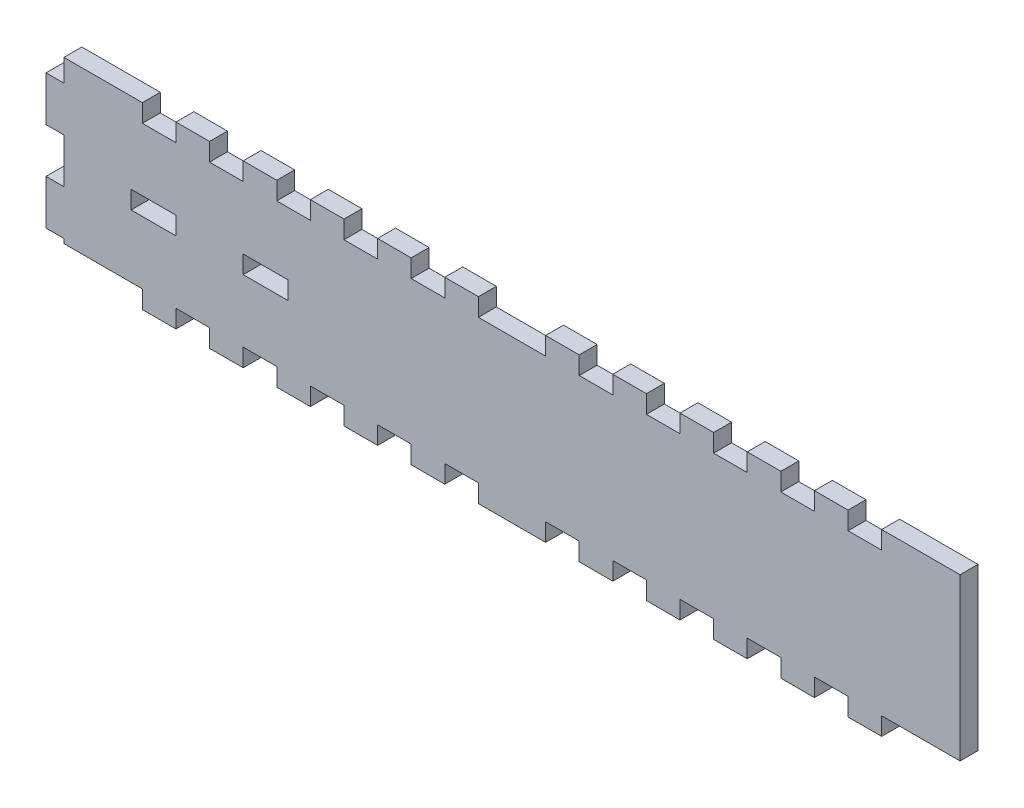
SolidWorks part; units mm, degrees
ref_plane "Plan de face" through (0, 0, 0) normal (0, 0, 1) x (1, 0, 0)
ref_plane "Plan de dessus" through (0, 0, 0) normal (0, 1, 0) x (1, 0, 0)
ref_plane "Plan de droite" through (0, 0, 0) normal (1, 0, 0) x (0, 0, -1)
sketch "Esquisse1" plane through (0, 0, 0) normal (0, 0, 1) x (1, 0, 0)
  line L1 (-200, -40) -> (200, -40)
  line L2 (-200, -40) -> (-200, 40)
  line L3 (-200, 40) -> (200, 40)
  line L4 (200, -40) -> (200, 40)
  line L5 (-200, -40) -> (200, 40) construction
  line L6 (-200, 40) -> (200, -40) construction
  point P0 (0, 0)
  dimension "D1" = 400
  dimension "D2" = 80
extrude "Boss.-Extru.1" add sketch "Esquisse1" along normal blind 8
sketch "Esquisse2" plane through (0, 0, 0) normal (0, 0, 1) x (1, 0, 0)
  line L0 (-200, 40) -> (-200, -40) construction
  line L1 (-200, 10) -> (-208, 10)
  line L2 (-200, 10) -> (-200, 30)
  line L3 (-200, 30) -> (-208, 30)
  line L4 (-208, 10) -> (-208, 30)
  line L5 (-200, 0) -> (-152.7974, 0) construction
  line L6 (-200, -30) -> (-208, -30)
  line L7 (-208, -10) -> (-208, -30)
  line L8 (-200, -10) -> (-208, -10)
  line L9 (-200, -10) -> (-200, -30)
  point P6 (-200, 0)
  dimension "D1" = 10
  dimension "D2" = 20
  dimension "D3" = 8
extrude "Boss.-Extru.2" add sketch "Esquisse2" along normal blind 8
sketch "Esquisse4" plane through (0, 0, 0) normal (0, 0, 1) x (1, 0, 0)
  line L0 (200, 40) -> (-200, 40) construction
  line L1 (0, 40) -> (-15, 40)
  line L3 (0, 32) -> (-15, 32)
  line L4 (-15, 40) -> (-15, 32)
  line L5 (-30, 40) -> (-30, 32)
  line L6 (-30, 40) -> (-45, 40)
  line L7 (-45, 40) -> (-45, 32)
  line L8 (-30, 32) -> (-45, 32)
  line L9 (-60, 40) -> (-60, 32)
  line L10 (-60, 40) -> (-75, 40)
  line L11 (-75, 40) -> (-75, 32)
  line L12 (-60, 32) -> (-75, 32)
  line L13 (-90, 40) -> (-90, 32)
  line L14 (-90, 40) -> (-105, 40)
  line L15 (-105, 40) -> (-105, 32)
  line L16 (-90, 32) -> (-105, 32)
  line L17 (-120, 40) -> (-120, 32)
  line L18 (-120, 40) -> (-135, 40)
  line L19 (-135, 40) -> (-135, 32)
  line L20 (-120, 32) -> (-135, 32)
  line L21 (-150, 40) -> (-150, 32)
  line L22 (-150, 40) -> (-165, 40)
  line L23 (-165, 40) -> (-165, 32)
  line L24 (-150, 32) -> (-165, 32)
  line L25 (0, 0) -> (0, 21.1046) construction
  line L26 (30, 40) -> (45, 40)
  line L27 (45, 40) -> (45, 32)
  line L28 (30, 32) -> (45, 32)
  line L29 (30, 40) -> (30, 32)
  line L30 (60, 40) -> (75, 40)
  line L31 (75, 40) -> (75, 32)
  line L32 (60, 32) -> (75, 32)
  line L33 (60, 40) -> (60, 32)
  line L34 (90, 40) -> (105, 40)
  line L35 (105, 40) -> (105, 32)
  line L36 (90, 32) -> (105, 32)
  line L37 (90, 40) -> (90, 32)
  line L38 (120, 40) -> (135, 40)
  line L39 (135, 40) -> (135, 32)
  line L40 (120, 32) -> (135, 32)
  line L41 (120, 40) -> (120, 32)
  line L42 (150, 40) -> (165, 40)
  line L43 (165, 40) -> (165, 32)
  line L44 (150, 32) -> (165, 32)
  line L45 (150, 40) -> (150, 32)
  line L47 (0, 40) -> (15, 40)
  line L49 (0, 32) -> (15, 32)
  line L50 (15, 40) -> (15, 32)
  dimension "D1" = 15
  dimension "D2" = 8
  dimension "D4" = 15
  dimension "D3" = 6
extrude "Enlèv. mat.-Extru.1" cut sketch "Esquisse4" along normal through all
sketch "Esquisse5" plane through (0, 0, 0) normal (0, 0, 1) x (1, 0, 0)
  line L0 (-200, -40) -> (200, -40) construction
  line L1 (-15, -40) -> (-30, -40)
  line L2 (-15, -40) -> (-15, -32)
  line L3 (-15, -32) -> (-30, -32)
  line L4 (-30, -40) -> (-30, -32)
  line L5 (-45, -40) -> (-45, -32)
  line L6 (-45, -40) -> (-60, -40)
  line L7 (-60, -40) -> (-60, -32)
  line L8 (-45, -32) -> (-60, -32)
  line L9 (-75, -40) -> (-75, -32)
  line L10 (-75, -40) -> (-90, -40)
  line L11 (-90, -40) -> (-90, -32)
  line L12 (-75, -32) -> (-90, -32)
  line L13 (-105, -40) -> (-105, -32)
  line L14 (-105, -40) -> (-120, -40)
  line L15 (-120, -40) -> (-120, -32)
  line L16 (-105, -32) -> (-120, -32)
  line L17 (-135, -40) -> (-135, -32)
  line L18 (-135, -40) -> (-150, -40)
  line L19 (-150, -40) -> (-150, -32)
  line L20 (-135, -32) -> (-150, -32)
  line L22 (0, 0) -> (0, -22.7254) construction
  line L23 (-200, -40) -> (-165, -40)
  line L24 (-200, -40) -> (-200, -32)
  line L25 (-200, -32) -> (-165, -32)
  line L26 (-165, -40) -> (-165, -32)
  line L27 (15, -32) -> (30, -32)
  line L28 (30, -40) -> (30, -32)
  line L29 (15, -40) -> (30, -40)
  line L30 (15, -40) -> (15, -32)
  line L31 (45, -40) -> (60, -40)
  line L32 (60, -40) -> (60, -32)
  line L33 (45, -32) -> (60, -32)
  line L34 (45, -40) -> (45, -32)
  line L35 (75, -40) -> (90, -40)
  line L36 (90, -40) -> (90, -32)
  line L37 (75, -32) -> (90, -32)
  line L38 (75, -40) -> (75, -32)
  line L39 (105, -40) -> (120, -40)
  line L40 (120, -40) -> (120, -32)
  line L41 (105, -32) -> (120, -32)
  line L42 (105, -40) -> (105, -32)
  line L43 (135, -40) -> (150, -40)
  line L44 (150, -40) -> (150, -32)
  line L45 (135, -32) -> (150, -32)
  line L46 (135, -40) -> (135, -32)
  line L47 (200, -32) -> (165, -32)
  line L48 (165, -40) -> (165, -32)
  line L49 (200, -40) -> (165, -40)
  line L50 (200, -40) -> (200, -32)
  point P6 (0, -40)
  dimension "D1" = 15
  dimension "D2" = 8
  dimension "D3" = 15
  dimension "D5" = 35
  dimension "D6" = 8
  dimension "D4" = 5
extrude "Enlèv. mat.-Extru.2" cut sketch "Esquisse5" along normal through all
sketch "Esquisse6" plane through (0, 0, 0) normal (0, 0, 1) x (1, 0, 0)
  line L0 (-200, 10) -> (-200, -10) construction
  line L1 (-170, -4) -> (-150, -4)
  line L2 (-170, -4) -> (-170, 4)
  line L3 (-170, 4) -> (-150, 4)
  line L4 (-150, -4) -> (-150, 4)
  line L5 (-170, -4) -> (-150, 4) construction
  line L6 (-170, 4) -> (-150, -4) construction
  line L7 (-120, -4) -> (-120, 4)
  line L8 (-120, -4) -> (-100, -4)
  line L9 (-100, -4) -> (-100, 4)
  line L10 (-120, 4) -> (-100, 4)
  point P0 (-160, 0)
  point P7 (-200, 0)
  dimension "D1" = 30
  dimension "D2" = 20
  dimension "D3" = 8
  dimension "D4" = 2
extrude "Enlèv. mat.-Extru.3" cut sketch "Esquisse6" along normal through all
